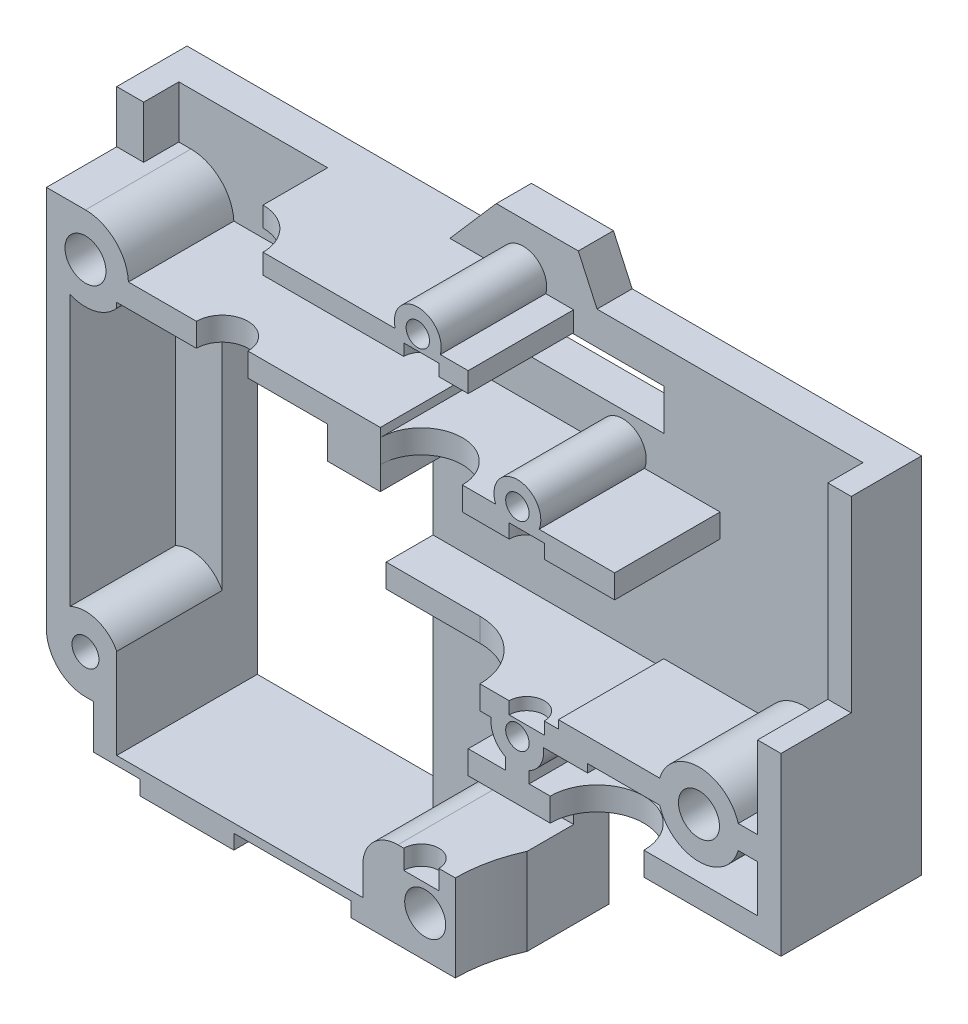
SolidWorks part; units mm, degrees
ref_plane "Plan de face" through (0, 0, 0) normal (0, 0, 1) x (1, 0, 0)
ref_plane "Plan de dessus" through (0, 0, 0) normal (0, 1, 0) x (1, 0, 0)
ref_plane "Plan de droite" through (0, 0, 0) normal (1, 0, 0) x (0, 0, -1)
sketch "Esquisse1" plane through (0, 0, 0) normal (0, 0, 1) x (1, 0, 0)
  line L0 (-11.0061, -13.4188) -> (-11.0061, 16.5812) construction
  line L1 (-12.3061, 57.5812) -> (-12.3061, 54.5812)
  line L2 (-17.0061, 57.5812) -> (-17.0061, -8.5888)
  line L3 (-9.0061, -16.9188) -> (-1.0061, -16.9188)
  line L4 (18.9939, -1.4188) -> (18.9939, -16.9188)
  line L5 (-11.0061, -13.4188) -> (6.9939, -13.4188) construction
  line L6 (6.9939, 16.5812) -> (6.9939, -13.4188) construction
  line L7 (18.9939, -1.4188) -> (45.6939, -1.4188)
  line L8 (45.6939, -1.4188) -> (45.6939, 29.5812)
  line L9 (45.6939, 29.5812) -> (20.9939, 29.5812)
  line L10 (20.9939, 29.5812) -> (19.3939, 33.0812)
  line L11 (19.3939, 33.0812) -> (12.3939, 33.0812)
  line L12 (-12.3061, 54.5812) -> (12.3939, 33.0812)
  line L13 (-13.6761, -11.9188) -> (-13.0061, -11.9188)
  line L14 (-17.0061, 57.5812) -> (-12.3061, 57.5812)
  line L15 (-13.0061, -11.9188) -> (-13.0061, -15.6688)
  line L16 (-13.0061, -15.6688) -> (-9.0061, -15.6688)
  line L17 (-9.0061, -15.6688) -> (-9.0061, -16.9188)
  line L18 (-1.0061, -16.9188) -> (-1.0061, -15.6688)
  line L19 (-1.0061, -15.6688) -> (8.9939, -15.6688)
  line L20 (8.9939, -15.6688) -> (8.9939, -16.9188)
  line L21 (8.9939, -16.9188) -> (18.9939, -16.9188)
  line L22 (6.9939, 18.5812) -> (-11.0061, 18.5812) construction
  line L23 (-4.2061, -14.9188) -> (0.1939, -14.9188) construction
  line L26 (-11.0061, -14.9188) -> (-11.0061, 18.5812)
  line L27 (6.9939, 18.5812) -> (-11.0061, 18.5812)
  line L28 (6.9939, 18.5812) -> (6.9939, -14.9188)
  line L30 (-11.0061, -14.9188) -> (6.9939, -14.9188)
  arc A0 (-17.0061, -8.5888) -> (-13.6761, -11.9188) centre (-13.6761, -8.5888) ccw
  circle A1 centre (-13.6761, -8.5888) radius 1.15
  circle A2 centre (-13.6761, 20.4112) radius 1.75
  circle A3 centre (15.3239, -13.4188) radius 1.75
  circle A4 centre (38.6939, 5.5812) radius 1.75
  circle A5 centre (23.1939, 3.5812) radius 1
  circle A6 centre (23.1939, 20.5812) radius 1
  circle A7 centre (14.6939, 29.0812) radius 1
  dimension "D19" = 6.66
  dimension "D20" = 2.3
  dimension "D21" = 3.5
  dimension "D24" = 3.5
  dimension "D26" = 3.5
  dimension "D27" = 7
  dimension "D29" = 2
  dimension "D31" = 22.5
  dimension "D32" = 2
  dimension "D34" = 2
  dimension "D1" = 6
  dimension "D2" = 3.5
  dimension "D3" = 12
  dimension "D4" = 15.5
  dimension "D5" = 26.7
  dimension "D6" = 31
  dimension "D7" = 24.7
  dimension "D8" = 3.5
  dimension "D9" = 4
  dimension "D10" = 4.7
  dimension "D11" = 3
  dimension "D12" = 29.4
  dimension "D13" = 7
  dimension "D14" = 8
  dimension "D15" = 8
  dimension "D16" = 10
  dimension "D17" = 1.25
  dimension "D18" = 5
  dimension "D22" = 29
  dimension "D23" = 29
  dimension "D25" = 3.5
  dimension "D28" = 7
  dimension "D30" = 5
  dimension "D33" = 17
  dimension "D35" = 8.5
  dimension "D36" = 8.5
extrude "Boss.-Extru.2" add sketch "Esquisse1" along normal blind 12
ref_plane "Plan1" through (0, 0, 3) normal (0, 0, 1) x (1, 0, 0)
sketch "Esquisse2" plane through (0, 0, 3) normal (0, 0, 1) x (1, 0, 0)
  line L0 (-15.0061, -5.8997) -> (-15.0061, 17.1737)
  line L1 (-17.0061, 57.5812) -> (-17.0061, -8.5888) construction
  line L2 (-11.0061, 18.5812) -> (-11.0061, -14.9188) construction
  line L3 (-11.0061, 18.1482) -> (-11.0061, -7.2209)
  line L4 (-14.7061, 24.0812) -> (-13.6761, 24.0812)
  line L5 (-10.01, 20.5812) -> (11.4939, 20.5812)
  line L7 (6.9939, 5.8812) -> (6.9939, 15.8312)
  line L8 (6.9939, -14.9188) -> (6.9939, 18.5812) construction
  line L9 (6.9939, -14.9188) -> (6.9939, 3.8812)
  line L10 (-9.0061, -16.9188) -> (-1.0061, -16.9188) construction
  line L11 (11.4939, 20.5812) -> (11.4939, 19.8312)
  line L13 (-17.0061, 57.5812) -> (-17.0061, -8.5888) construction
  line L14 (-14.7061, 24.0812) -> (-14.7061, 57.5812)
  line L15 (-12.3061, 57.5812) -> (-17.0061, 57.5812) construction
  line L16 (-12.3061, 54.5812) -> (-12.3061, 57.5812) construction
  line L17 (12.3939, 33.0812) -> (-12.3061, 54.5812) construction
  line L18 (-12.3061, 57.5812) -> (-14.7061, 57.5812)
  line L19 (-12.3061, 54.5812) -> (-12.3061, 57.5812)
  line L20 (12.3939, 33.0812) -> (-12.3061, 54.5812)
  line L21 (19.3939, 33.0812) -> (12.3939, 33.0812) construction
  line L22 (19.3939, 33.0812) -> (12.3939, 33.0812)
  line L23 (20.9939, 29.5812) -> (19.3939, 33.0812) construction
  line L24 (20.9939, 29.5812) -> (19.3939, 33.0812)
  line L25 (45.6939, 29.5812) -> (20.9939, 29.5812) construction
  line L26 (43.6939, 29.5812) -> (20.9939, 29.5812)
  line L27 (43.6939, 29.5812) -> (43.6939, 6.5812)
  line L28 (45.6939, -1.4188) -> (45.6939, 29.5812) construction
  line L29 (43.6939, 6.5812) -> (42.048, 6.5812)
  line L30 (26.6939, 6.5812) -> (26.6939, 5.8812)
  line L31 (26.6939, 5.8812) -> (6.9939, 5.8812)
  line L32 (43.6939, 4.5812) -> (42.048, 4.5812)
  line L33 (29.1939, 4.5812) -> (29.1939, 3.8812)
  line L34 (29.1939, 3.8812) -> (25.4238, 3.8812)
  line L35 (43.6939, 0.5812) -> (24.1939, 0.5812)
  line L36 (18.9939, -1.4188) -> (45.6939, -1.4188) construction
  line L37 (24.1939, 1.5656) -> (24.1939, 0.5812)
  line L38 (22.1939, 1.5656) -> (22.1939, 0.5812)
  line L39 (20.964, 3.8812) -> (6.9939, 3.8812)
  line L40 (11.4939, 15.8312) -> (6.9939, 15.8312)
  line L42 (35.3398, 6.5812) -> (26.6939, 6.5812)
  line L43 (35.3398, 4.5812) -> (29.1939, 4.5812)
  line L44 (6.9939, -14.9188) -> (9.9939, -14.9188)
  line L45 (9.9939, -14.9188) -> (9.9939, -9.5188)
  line L46 (9.9939, -9.5188) -> (18.9939, -9.5188)
  line L47 (18.9939, -16.9188) -> (18.9939, -1.4188) construction
  line L48 (8.9939, -16.9188) -> (18.9939, -16.9188) construction
  line L49 (18.9939, -9.5188) -> (18.9939, 0.5812)
  line L50 (22.1939, 0.5812) -> (18.9939, 0.5812)
  line L51 (6.9939, 5.8812) -> (6.9939, 15.8312)
  line L52 (11.4939, 19.8312) -> (21.3399, 19.8312)
  line L53 (31.4939, 19.8312) -> (31.4939, 17.8312)
  line L54 (31.4939, 17.8312) -> (11.4939, 17.8312)
  line L55 (11.4939, 17.8312) -> (11.4939, 15.8312)
  line L56 (25.048, 19.8312) -> (31.4939, 19.8312)
  line L57 (-2.0061, -13.4188) -> (-2.0061, 16.5812) construction
  line L58 (18.9939, 26.8312) -> (-2.0061, 26.8312)
  line L59 (18.9939, 26.8312) -> (18.9939, 28.5312)
  line L60 (18.9939, 28.5312) -> (16.6168, 28.5312)
  line L61 (-2.0061, 26.8312) -> (-2.0061, 28.5312)
  line L62 (12.771, 28.5312) -> (-2.0061, 28.5312)
  line L63 (43.6939, 4.5812) -> (43.6939, 0.5812)
  arc A0 (-11.0061, -7.2209) -> (-15.0061, -5.8997) centre (-13.6761, -8.5888) ccw
  arc A1 (-15.0061, 17.1737) -> (-11.0061, 18.1482) centre (-13.6761, 20.4112) ccw
  arc A2 (-10.01, 20.5812) -> (-13.6761, 24.0812) centre (-13.6761, 20.4112) ccw
  arc A3 (42.048, 6.5812) -> (35.3398, 6.5812) centre (38.6939, 5.5812) ccw
  arc A5 (25.048, 19.8312) -> (21.3399, 19.8312) centre (23.1939, 20.5812) ccw
  arc A6 (20.964, 3.8812) -> (22.1939, 1.5656) centre (23.1939, 3.5812) ccw
  arc A7 (35.3398, 4.5812) -> (42.048, 4.5812) centre (38.6939, 5.5812) ccw
  arc A8 (24.1939, 1.5656) -> (25.4238, 3.8812) centre (23.1939, 3.5812) ccw
  arc A9 (16.6168, 28.5312) -> (12.771, 28.5312) centre (14.6939, 29.0812) ccw
  dimension "D2" = 6
  dimension "D3" = 7
  dimension "D8" = 7
  dimension "D18" = 4.5
  dimension "D26" = 4
  dimension "D30" = 4
  dimension "D1" = 2
  dimension "D4" = 41
  dimension "D5" = 37.5
  dimension "D6" = 2.3
  dimension "D7" = 2
  dimension "D9" = 2
  dimension "D10" = 1
  dimension "D11" = 2
  dimension "D12" = 2
  dimension "D13" = 2.7
  dimension "D14" = 14.5
  dimension "D15" = 2.5
  dimension "D16" = 2
  dimension "D17" = 1
  dimension "D19" = 28.5
  dimension "D20" = 4.75
  dimension "D21" = 7.4
  dimension "D22" = 9
  dimension "D23" = 2
  dimension "D24" = 20
  dimension "D25" = 2
  dimension "D27" = 1.7
  dimension "D28" = 7
  dimension "D29" = 21
extrude "Enlèv. mat.-Extru.1" cut sketch "Esquisse2" along normal through all contours A5 L56 L53 L54 L55 L40 L7 L31 L30 L42 A3 L29 L27 L26 L24 L22 L20 L19 L18 L14 L4 A2 L5 L11 L52 A9 L60 L59 L58 L61 L62 | A6 L39 L9 L44 L45 L46 L49 L50 L38 | A1 L0 A0 L3 | A8 L37 L35 L63 L32 A7 L43 L33 L34
ref_plane "Plan2" through (0, 0, 6) normal (0, 0, 1) x (1, 0, 0)
sketch "Esquisse3" plane through (0, 0, 6) normal (0, 0, 1) x (1, 0, 0)
  line L0 (-14.7061, 24.0812) -> (-14.7061, 57.5812) construction
  line L1 (-17.0061, 57.5812) -> (-17.0061, -8.5888) construction
  line L2 (-14.7061, 24.0812) -> (-14.7061, 57.5812)
  line L3 (-17.0061, 57.5812) -> (-17.0061, 24.0812)
  line L4 (-14.7061, 24.0812) -> (-17.0061, 24.0812)
  line L5 (-14.7061, 57.5812) -> (-17.0061, 57.5812)
  line L7 (43.6939, 29.5812) -> (43.6939, 6.5812) construction
  line L8 (45.6939, -1.4188) -> (45.6939, 29.5812) construction
  line L9 (45.6939, 29.5812) -> (43.6939, 29.5812)
  line L10 (43.6939, 29.5812) -> (43.6939, 13.5812)
  line L11 (45.6939, 13.5812) -> (45.6939, 29.5812)
  line L12 (45.6939, 13.5812) -> (43.6939, 13.5812)
  dimension "D1" = 16
extrude "Enlèv. mat.-Extru.2" cut sketch "Esquisse3" along normal through all
fillet "Congé1" radius 3 1 edges at (9.9939, -9.5188, 7.5)
sketch "Esquisse4" plane through (0, 20.5812, 0) normal (0, 1, 0) x (1, 0, 0)
  circle A2 centre (-2.0061, -12) radius 2.2
extrude "Enlèv. mat.-Extru.3" cut sketch "Esquisse4" against normal up to next
sketch "Esquisse5" plane through (0, 28.5312, 0) normal (0, 1, 0) x (1, 0, 0)
  circle A2 centre (-2.0178, -12.0143) radius 3.5
extrude "Enlèv. mat.-Extru.4" cut sketch "Esquisse5" against normal up to next
sketch "Esquisse6" plane through (0, 19.8312, 0) normal (0, 1, 0) x (1, 0, 0)
  circle A2 centre (14.9939, -12) radius 3.5
extrude "Enlèv. mat.-Extru.5" cut sketch "Esquisse6" against normal blind 5
sketch "Esquisse7" plane through (0, 0, 3) normal (0, 0, 1) x (1, 0, 0)
  line L1 (6.0979, 30.2812) -> (-1.943, 30.2812)
  line L2 (6.0979, 30.2812) -> (6.0979, 32.0812)
  line L3 (6.0979, 32.0812) -> (-1.943, 32.0812)
  line L4 (-1.943, 30.2812) -> (-1.943, 32.0812)
  line L5 (-2.5017, 31.5812) -> (-3.1893, 31.5812) construction
  line L6 (-3.1893, 30.7812) -> (-2.5017, 30.7812) construction
  dimension "D1" = 0.5
  dimension "D2" = 0.5
extrude "Enlèv. mat.-Extru.6" cut sketch "Esquisse7" against normal blind 1
sketch "Esquisse8" plane through (0, 0, 2) normal (0, 0, 1) x (1, 0, 0)
  line L0 (-26.7441, 23.7426) -> (-3.2438, 23.7426) construction
  line L1 (26.6966, 23.2426) -> (2.5188, 23.2426)
  line L2 (26.6966, 23.2426) -> (26.6966, 26.7426)
  line L3 (26.6966, 26.7426) -> (2.5188, 26.7426)
  line L4 (2.5188, 23.2426) -> (2.5188, 26.7426)
  line L5 (-3.2438, 26.2426) -> (-26.7441, 26.2426) construction
  line L6 (26.6966, 26.7426) -> (26.6966, 23.2426) construction
  line L7 (2.5188, 23.2426) -> (2.5188, 26.7426) construction
  dimension "D1" = 0.5
  dimension "D2" = 0.5
extrude "Enlèv. mat.-Extru.7" cut sketch "Esquisse8" against normal through all and the other way blind 3
sketch "Esquisse9" plane through (0, 5.8812, 0) normal (0, 1, 0) x (1, 0, 0)
  line L1 (14.9939, -7) -> (6.9939, -7)
  line L3 (6.9939, -12) -> (6.9939, -7)
  line L6 (19.9939, -12) -> (6.9939, -12)
  arc A1 (14.9939, -7) -> (19.9939, -12) centre (14.9939, -12) cw
extrude "Enlèv. mat.-Extru.8" cut sketch "Esquisse9" against normal up to next
sketch "Esquisse10" plane through (0, 0.5812, 0) normal (0, 1, 0) x (1, 0, 0)
  circle A2 centre (29.9939, -12) radius 4
extrude "Enlèv. mat.-Extru.9" cut sketch "Esquisse10" against normal up to next
sketch "Esquisse11" plane through (0, -1.4188, 0) normal (0, -1, 0) x (1, 0, 0)
  circle A0 centre (29.9939, 12) radius 12.1
extrude "Enlèv. mat.-Extru.10" cut sketch "Esquisse11" along normal through all
sketch "Esquisse17" plane through (0, 26.8312, 0) normal (0, -1, 0) x (1, 0, 0)
  circle A2 centre (14.9939, 12) radius 1.5
extrude "Enlèv. mat.-Extru.11" cut sketch "Esquisse17" against normal blind 1 and the other way blind 38
sketch "Esquisse18" plane through (0, 17.8312, 0) normal (0, -1, 0) x (1, 0, 0)
  circle A1 centre (23.9939, 12) radius 1.5
extrude "Enlèv. mat.-Extru.12" cut sketch "Esquisse18" against normal blind 1.2 and the other way blind 13
sketch "Esquisse19" plane through (0, 0, 6) normal (0, 0, 1) x (1, 0, 0)
  line L0 (12.3939, 33.0812) -> (-12.3061, 54.5812) construction
  line L1 (-12.3061, 54.5812) -> (-12.3061, 57.5812) construction
  line L2 (-12.3061, 57.5812) -> (-14.7061, 57.5812) construction
  line L3 (12.3939, 33.0812) -> (-12.3061, 54.5812)
  line L4 (-17.0061, 24.0812) -> (-14.7061, 24.0812)
  line L5 (-14.7061, 24.0812) -> (-14.7061, 57.5812)
  line L6 (-14.7061, 57.5812) -> (-17.0061, 57.5812)
  line L7 (-17.0061, 57.5812) -> (-17.0061, 24.0812)
  line L10 (-14.7061, 57.5812) -> (-17.0061, 57.5812)
  line L11 (-17.0061, 57.5812) -> (-17.0061, 28.5312)
  line L12 (-12.3061, 54.5812) -> (-12.3061, 57.5812)
  line L13 (-12.3061, 57.5812) -> (-14.7061, 57.5812)
  line L14 (12.3939, 33.0812) -> (8.4334, 28.5312)
  line L15 (12.771, 28.5312) -> (-2.0061, 28.5312) construction
  line L16 (8.4334, 28.5312) -> (-17.0061, 28.5312)
  dimension "D1" = 0
extrude "Enlèv. mat.-Extru.13" cut sketch "Esquisse19" against normal blind 10
